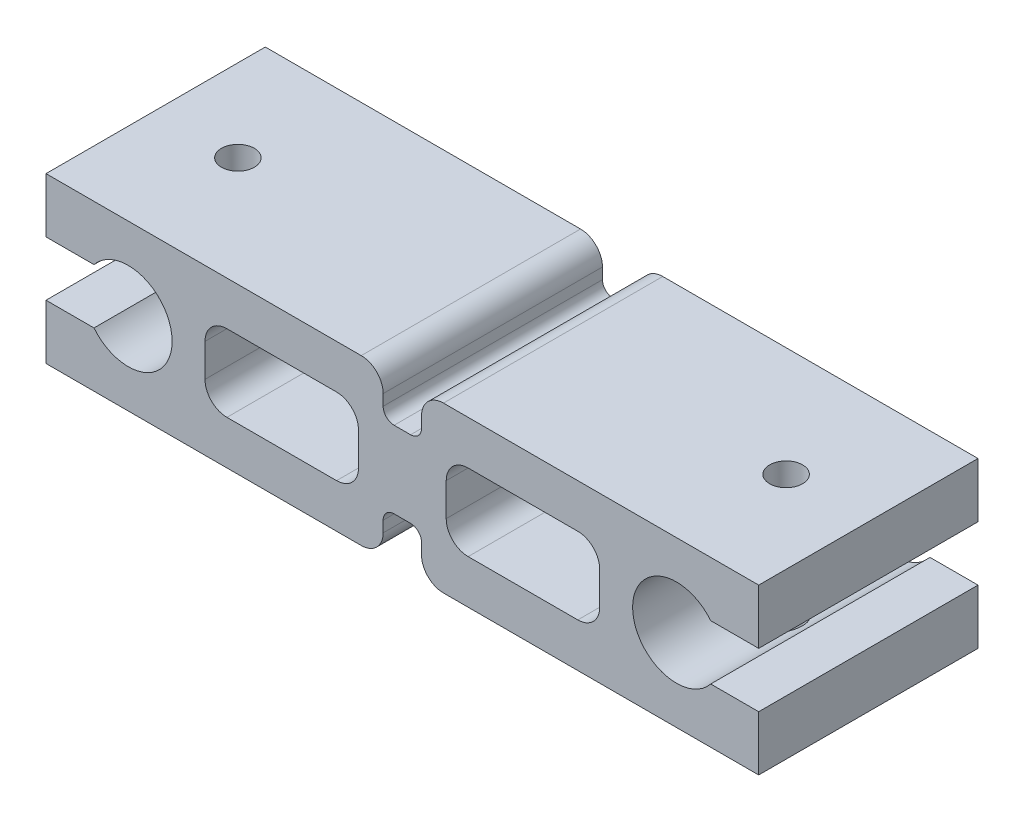
SolidWorks part; units mm, degrees
material "POM 乙缩醛共聚物"
ref_plane "前视基准面" through (0, 0, 0) normal (0, 0, 1) x (1, 0, 0)
ref_plane "上视基准面" through (0, 0, 0) normal (0, 1, 0) x (1, 0, 0)
ref_plane "右视基准面" through (0, 0, 0) normal (1, 0, 0) x (0, 0, -1)
sketch "草图1" plane through (0, 0, 0) normal (0, 0, 1) x (1, 0, 0)
  line L0 (0, 66.2957) -> (0, -61.4872) construction
  line L1 (-93.4951, 0) -> (103.0462, 0) construction
  line L2 (-25, 7.5) -> (25, 7.5)
  line L3 (-25, -7.5) -> (25, -7.5)
  line L4 (-25, 7.5) -> (-32.5, 7.5)
  line L5 (-32.5, 7.5) -> (-32.5, -7.5)
  line L6 (-32.5, -7.5) -> (-25, -7.5)
  line L7 (25, -7.5) -> (32.5, -7.5)
  line L8 (32.5, -7.5) -> (32.5, 7.5)
  line L9 (32.5, 7.5) -> (25, 7.5)
  circle A0 centre (-25, 0) radius 4
  circle A1 centre (25, 0) radius 4
  arc A2 (-25, 7.5) -> (-25, -7.5) centre (-25, 0) ccw construction
  arc A3 (25, -7.5) -> (25, 7.5) centre (25, 0) ccw construction
  dimension "D1" = 8
  dimension "D2" = 50
  dimension "D3" = 15
extrude "凸台-拉伸1" add sketch "草图1" along normal blind 20
sketch "草图2" plane through (0, 0, 20) normal (0, 0, 1) x (1, 0, 0)
  line L5 (0, 16.0342) -> (0, -21.1771) construction
  line L6 (-25, 0) -> (25, 0) construction
  line L7 (32.5, 7.5) -> (-32.5, 7.5) construction
  line L8 (-18, 3.5) -> (-4, 3.5)
  line L9 (-18, 3.5) -> (-18, -3.5)
  line L10 (-18, -3.5) -> (-4, -3.5)
  line L11 (-4, 3.5) -> (-4, -3.5)
  line L12 (-18, 3.5) -> (-4, -3.5) construction
  line L13 (-18, -3.5) -> (-4, 3.5) construction
  line L14 (4, 3.5) -> (18, 3.5)
  line L15 (4, 3.5) -> (4, -3.5)
  line L16 (4, -3.5) -> (18, -3.5)
  line L17 (18, 3.5) -> (18, -3.5)
  line L18 (4, 3.5) -> (18, -3.5) construction
  line L19 (4, -3.5) -> (18, 3.5) construction
  line L20 (-32.5, -7.5) -> (32.5, -7.5) construction
  line L21 (-1.75, 7.5) -> (1.75, 7.5)
  line L22 (-1.75, 7.5) -> (-1.75, 3.5)
  line L23 (-1.75, 3.5) -> (1.75, 3.5)
  line L24 (1.75, 7.5) -> (1.75, 3.5)
  line L25 (-1.75, -7.5) -> (1.75, -7.5)
  line L26 (-1.75, -7.5) -> (-1.75, -3.5)
  line L27 (-1.75, -3.5) -> (1.75, -3.5)
  line L28 (1.75, -7.5) -> (1.75, -3.5)
  circle A3 centre (25, 0) radius 4 construction
  point P4 (-11, 0)
  point P13 (11, 0)
  dimension "D1" = 3
  dimension "D2" = 8
  dimension "D3" = 4
  dimension "D4" = 3.5
  dimension "D5" = 4
extrude "切除-拉伸1" cut sketch "草图2" against normal through all
fillet "圆角1" radius 2 4 edges at (1.75, -7.5, 10) (-1.75, -7.5, 10) (1.75, 7.5, 10) (-1.75, 7.5, 10)
fillet "圆角2" radius 2 8 edges at (4, -3.5, 10) (18, -3.5, 10) (18, 3.5, 10) (4, 3.5, 10) (-18, 3.5, 10) (-18, -3.5, 10) (-4, -3.5, 10) (-4, 3.5, 10)
fillet "圆角4" radius 1 4 edges at (1.75, -3.5, 10) (-1.75, -3.5, 10) (1.75, 3.5, 10) (-1.75, 3.5, 10)
sketch "草图4" plane through (0, 7.5, 0) normal (0, 1, 0) x (1, 0, 0)
  line L0 (0, 17.721) -> (0, -40.163) construction
  line L1 (-32.5, -10) -> (36.9321, -10) construction
  line L2 (-32.5, -20) -> (-32.5, 0) construction
  circle A0 centre (-25, -10) radius 1.5
  circle A1 centre (25, -10) radius 1.5
  dimension "D1" = 50
  dimension "D2" = 3
extrude "切除-拉伸2" cut sketch "草图4" against normal through all both and the other way through all
sketch "草图5" plane through (0, 0, 20) normal (0, 0, 1) x (1, 0, 0)
  line L0 (0, 12.8221) -> (0, -22.4484) construction
  line L1 (-45.4292, 0) -> (43.5559, 0) construction
  line L2 (-32.5, 7.5) -> (-32.5, -7.5) construction
  line L3 (-32.5, 2.5) -> (-28.1225, 2.5)
  line L4 (-32.5, 2.5) -> (-32.5, -2.5)
  line L5 (-32.5, -2.5) -> (-28.1225, -2.5)
  line L6 (-28.1225, 2.5) -> (-28.1225, -2.5)
  line L7 (32.5, -7.5) -> (32.5, 7.5) construction
  line L8 (32.5, 2.5) -> (28.1225, 2.5)
  line L9 (32.5, 2.5) -> (32.5, -2.5)
  line L10 (32.5, -2.5) -> (28.1225, -2.5)
  line L11 (28.1225, 2.5) -> (28.1225, -2.5)
  circle A0 centre (-25, 0) radius 4 construction
  circle A1 centre (25, 0) radius 4 construction
  dimension "D1" = 5
extrude "切除-拉伸3" cut sketch "草图5" against normal through all
